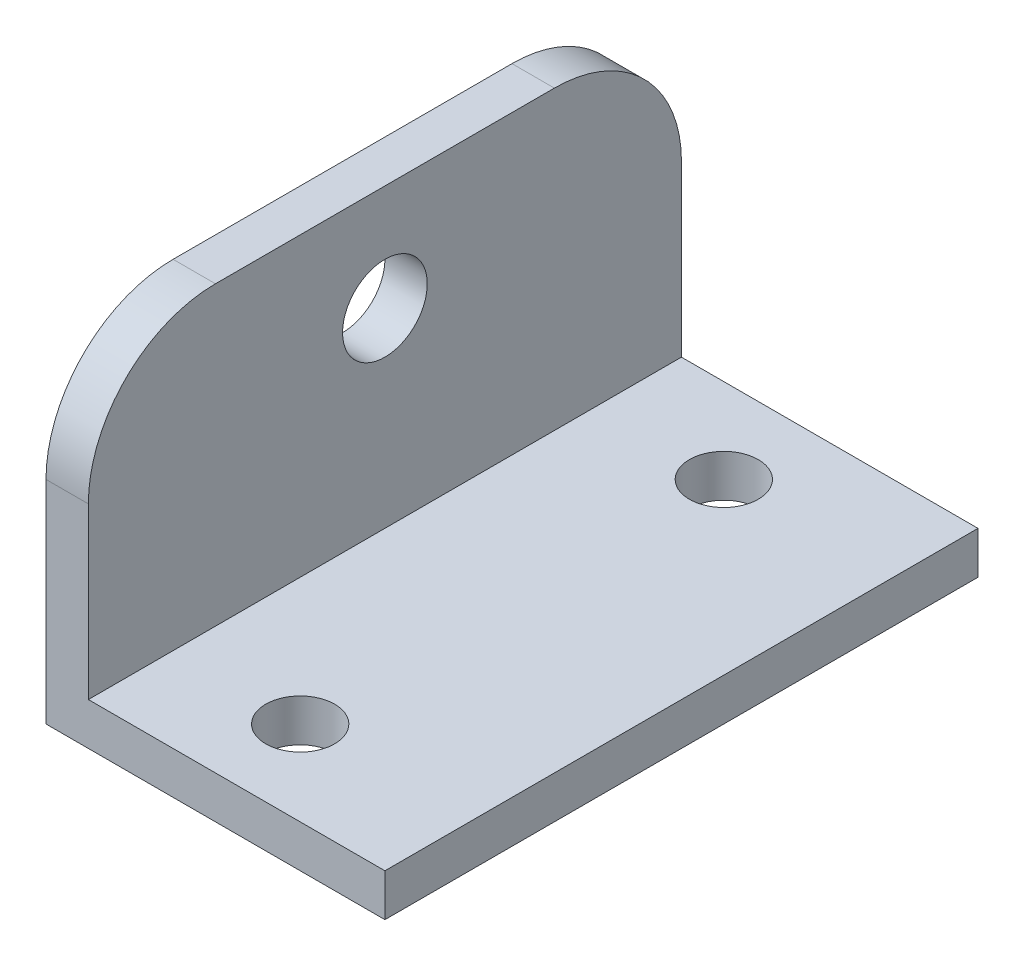
SolidWorks part; units mm, degrees
ref_plane "Front Plane" through (0, 0, 0) normal (0, 0, 1) x (1, 0, 0)
ref_plane "Top Plane" through (0, 0, 0) normal (0, 1, 0) x (1, 0, 0)
ref_plane "Right Plane" through (0, 0, 0) normal (1, 0, 0) x (0, 0, -1)
sketch "Sketch1" plane through (0, 0, 0) normal (0, 0, 1) x (1, 0, 0)
  line L0 (0, 0) -> (0, 25.4)
  line L1 (0, 0) -> (25.4, 0)
  line L2 (3.175, 3.175) -> (25.4, 3.175)
  line L3 (3.175, 3.175) -> (3.175, 25.4)
  line L4 (0, 25.4) -> (3.175, 25.4)
  line L5 (25.4, 0) -> (25.4, 3.175)
  dimension "D1" = 25.4
  dimension "D2" = 25.4
  dimension "D3" = 3.175
extrude "Boss-Extrude1" add sketch "Sketch1" along normal blind 44.45
hole_wizard "1/4 (0.25) Diameter Hole2" positions "Sketch10" profile "Sketch9" hole size "1/4" standard "ANSI Inch" end condition through all
sketch "Sketch10" plane through (0, 0, 0) normal (-1, 0, 0) x (0, 0, 1)
  line L1 (0, 17.4625) -> (44.45, 17.4625) construction
  line L2 (0, 25.4) -> (0, 0) construction
  line L3 (44.45, 25.4) -> (44.45, 0) construction
  line L5 (44.45, 25.4) -> (0, 25.4) construction
  point P12 (22.225, 17.4625)
  dimension "D1" = 7.9375
sketch "Sketch9" plane through (0, 17.4625, 22.225) normal (0, 1, 0) x (0, 0, 1)
  line L0 (0, 0) -> (0, 25.4)
  line L1 (0, 25.4) -> (3.175, 25.4)
  line L2 (3.175, 25.4) -> (3.175, 0)
  line L5 (3.175, 0) -> (0, 0)
  line L11 (0, -6.35) -> (0, 107.95) construction
  dimension "Thru Hole Dia." = 6.35
  dimension "Thru Hole Depth" = 25.4
fillet "Fillet1" radius 9.525 2 edges at (1.5875, 25.4, 0) (1.5875, 25.4, 44.45)
hole_wizard "13/64 (0.20313) Diameter Hole1" positions "Sketch12" profile "Sketch11" hole size "13/64" standard "ANSI Inch" end condition through all
sketch "Sketch12" plane through (0, 0, 0) normal (0, -1, 0) x (-1, 0, 0)
  line L0 (-12.7, -44.45) -> (-12.7, 0) construction
  line L1 (0, -44.45) -> (-25.4, -44.45) construction
  line L2 (0, 0) -> (-25.4, 0) construction
  point P9 (-12.7, -38.1)
  point P11 (-12.7, -6.35)
  dimension "D1" = 6.35
  dimension "D2" = 6.35
sketch "Sketch11" plane through (12.7, 0, 38.1) normal (1, 0, 0) x (0, 0, -1)
  line L0 (0, 0) -> (0, 25.4)
  line L1 (0, 25.4) -> (2.5797, 25.4)
  line L2 (2.5797, 25.4) -> (2.5797, 0)
  line L5 (2.5797, 0) -> (0, 0)
  line L11 (0, -6.35) -> (0, 107.95) construction
  dimension "Thru Hole Dia." = 5.1594
  dimension "Thru Hole Depth" = 25.4
